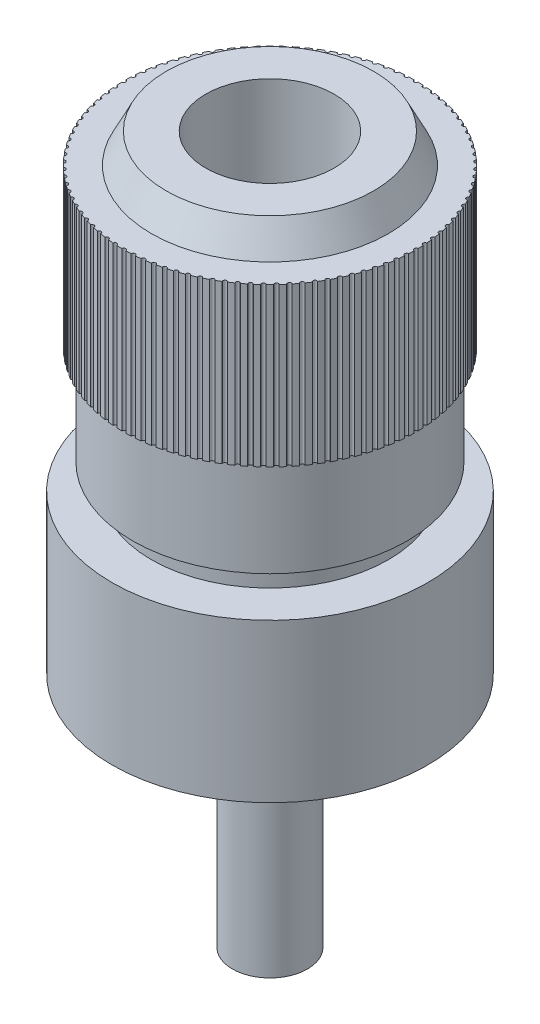
SolidWorks part; units mm, degrees
ref_plane "Alzado" through (0, 0, 0) normal (0, 0, 1) x (1, 0, 0)
ref_plane "Planta" through (0, 0, 0) normal (0, 1, 0) x (1, 0, 0)
ref_plane "Vista lateral" through (0, 0, 0) normal (1, 0, 0) x (0, 0, -1)
sketch "Croquis1" plane through (0, 0, 0) normal (0, 1, 0) x (1, 0, 0)
  circle A0 centre (0, 0) radius 6
  circle A1 centre (0, 0) radius 2.25
  dimension "D1" = 12
  dimension "D2" = 4.5
extrude "Saliente-Extruir1" add sketch "Croquis1" along normal blind 0.7
sketch "Croquis3" plane through (0, 0.7, 0) normal (0, 1, 0) x (1, 0, 0)
  circle A0 centre (0, 0) radius 8
  circle A1 centre (0, 0) radius 2.25 construction
  circle A2 centre (0, 0) radius 2.25
  dimension "D1" = 16
extrude "Saliente-Extruir2" add sketch "Croquis3" along normal blind 8
sketch "Croquis6" plane through (0, 8.7, 0) normal (0, 1, 0) x (1, 0, 0)
  circle A0 centre (0, 0) radius 1.9
  dimension "D1" = 3.8
extrude "Saliente-Extruir3" add sketch "Croquis6" against normal blind 20 separate body
sketch "Croquis7" plane through (0, 8.7, 0) normal (0, 1, 0) x (1, 0, 0)
  circle A0 centre (0, 0) radius 6
  dimension "D1" = 12
extrude "Saliente-Extruir4" add sketch "Croquis7" along normal blind 1.3
sketch "Croquis8" plane through (0, 10, 0) normal (0, 1, 0) x (1, 0, 0)
  circle A0 centre (0, 0) radius 2.8
  circle A1 centre (0, 0) radius 1.75
  point P5 (0, 0.2308)
  dimension "D1" = 5.6
  dimension "D2" = 3.5
extrude "Saliente-Extruir5" add sketch "Croquis8" along normal blind 10
sketch "Croquis9" plane through (0, 10, 0) normal (0, 1, 0) x (1, 0, 0)
  circle A0 centre (0, 0) radius 7.4
  circle A1 centre (0, 0) radius 3.25
  dimension "D1" = 14.8
  dimension "D2" = 6.5
extrude "Saliente-Extruir6" add sketch "Croquis9" along normal blind 14.5
sketch "Croquis11" plane through (0, 0, 0) normal (0, 0, 1) x (1, 0, 0)
  line L0 (0, 0) -> (0, 40.7671) construction
  line L1 (0, 24.5) -> (-5.25, 24.5)
  line L2 (7.4, 24.5) -> (-7.4, 24.5) construction
  line L3 (-5.25, 24.5) -> (-6, 23)
  line L4 (-6, 23) -> (-7.4, 23)
  line L5 (-7.4, 24.5) -> (-7.4, 10) construction
  line L6 (-7.4, 23) -> (-7.4, 24.5)
  line L7 (-7.4, 24.5) -> (-5.25, 24.5)
  line L8 (-6.95, 10) -> (-6.95, 15)
  line L9 (-7.4, 10) -> (7.4, 10) construction
  line L10 (-6.95, 15) -> (-7.4, 15)
  line L11 (-7.4, 15) -> (-7.4, 10)
  line L12 (-7.4, 10) -> (-6.95, 10)
  dimension "D1" = 5.25
  dimension "D2" = 1.5
  dimension "D3" = 6
  dimension "D4" = 5
  dimension "D5" = 6.95
revolve "Cortar-Revolución1" cut sketch "Croquis11" angle 360 about L0
sketch "Croquis12" plane through (0, 23, 0) normal (0, 1, 0) x (1, 0, 0)
  circle A0 centre (0, 0) radius 7.4 construction
  circle A1 centre (0, 0) radius 7.4
  arc A2 (0.1, -7.3993) -> (-0.1, -7.3993) centre (0, -7.4) ccw
  dimension "D1" = 0.1
extrude "Cortar-Extruir1" cut sketch "Croquis12" against normal blind 9.5 contours A1 A2
pattern_circular "MatrizC1" count 100 over 360 about axis through (0, 0, 0) along (0, 1, 0) of "Cortar-Extruir1"
